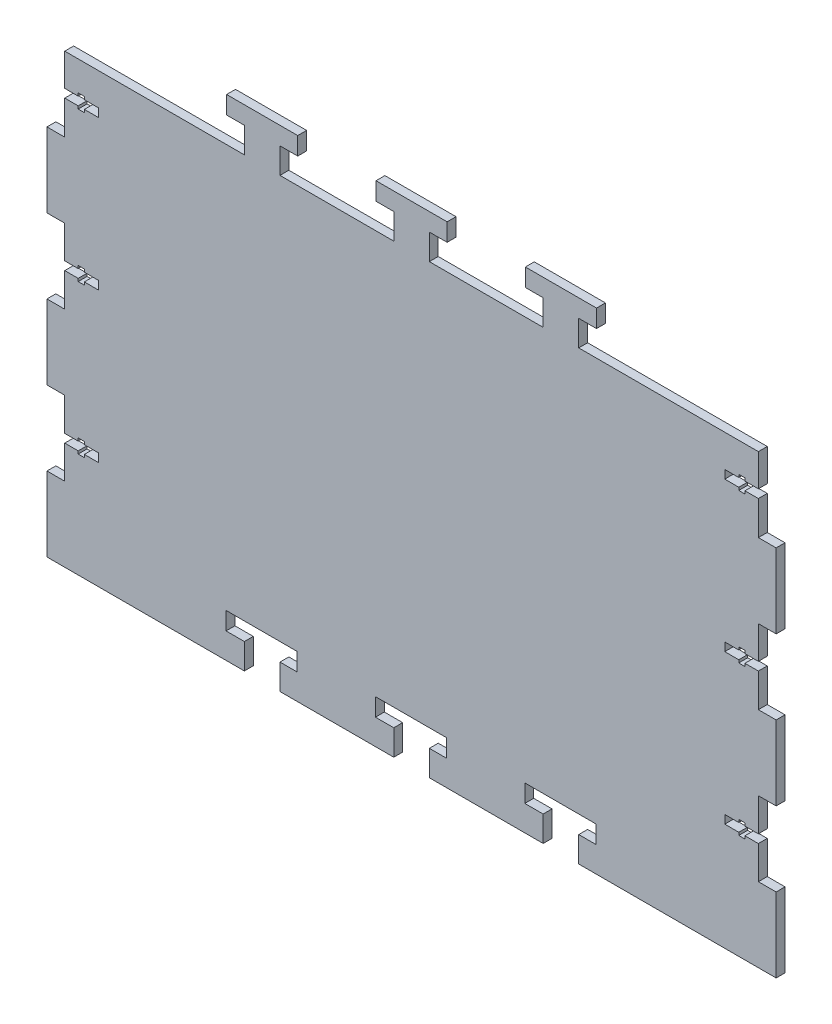
SolidWorks part; units mm, degrees
ref_plane "Front Plane" through (0, 0, 0) normal (0, 0, 1) x (1, 0, 0)
ref_plane "Top Plane" through (0, 0, 0) normal (0, 1, 0) x (1, 0, 0)
ref_plane "Right Plane" through (0, 0, 0) normal (1, 0, 0) x (0, 0, -1)
sketch "Sketch1" plane through (0, 0, 0) normal (0, 0, 1) x (1, 0, 0)
  line L1 (130.175, -79.7965) -> (-130.175, -79.7965)
  line L2 (130.175, -79.7965) -> (130.175, 79.7965)
  line L3 (130.175, 79.7965) -> (-130.175, 79.7965)
  line L4 (-130.175, -79.7965) -> (-130.175, 79.7965)
  line L5 (130.175, -79.7965) -> (-130.175, 79.7965) construction
  line L6 (130.175, 79.7965) -> (-130.175, -79.7965) construction
  point P0 (0, 0)
  dimension "D1" = 260.35
  dimension "D2" = 159.5929
extrude "Boss-Extrude1" add sketch "Sketch1" along normal blind 3.175
sketch "Sketch2" plane through (-130.175, 0, 0) normal (-1, 0, 0) x (0, 0, 1)
  line L0 (0, 79.7965) -> (0, -79.7965) construction
  line L1 (3.175, 79.7965) -> (0, 79.7965)
  line L2 (3.175, 79.7965) -> (3.175, 53.1976)
  line L3 (3.175, 53.1976) -> (0, 53.1976)
  line L4 (0, 79.7965) -> (0, 53.1976)
  dimension "D1" = 26.5988
extrude "Cut-Extrude1" cut sketch "Sketch2" against normal blind 6.35
pattern_linear "LPattern1" count 3 spacing 53.1976 along (0, -1, 0) of "Cut-Extrude1"
sketch "Sketch3" plane through (130.175, 0, 0) normal (1, 0, 0) x (0, 0, -1)
  line L0 (0, -79.7965) -> (0, 79.7965) construction
  line L1 (-3.175, -53.1976) -> (0, -53.1976)
  line L2 (-3.175, -53.1976) -> (-3.175, -26.5988)
  line L3 (-3.175, -26.5988) -> (0, -26.5988)
  line L4 (0, -53.1976) -> (0, -26.5988)
  line L6 (-3.175, 79.7965) -> (0, 79.7965) construction
  point P9 (-1.5875, 79.7965)
  dimension "D1" = 26.5988
  dimension "D2" = 106.3953
extrude "Cut-Extrude3" cut sketch "Sketch3" against normal blind 6.35
pattern_linear "LPattern3" count 3 spacing 53.1976 along (0, 1, 0) of "Cut-Extrude3"
sketch "Sketch5" plane through (-123.825, 0, 0) normal (-1, 0, 0) x (0, 0, 1)
  line L0 (0, -39.8982) -> (3.175, -39.8982) construction
  line L1 (0, -26.5988) -> (0, -53.1976) construction
  line L2 (3.175, -53.1976) -> (3.175, -26.5988) construction
  line L4 (3.175, -41.3982) -> (0, -41.3982)
  line L5 (3.175, -41.3982) -> (3.175, -38.3982)
  line L6 (3.175, -38.3982) -> (0, -38.3982)
  line L7 (0, -41.3982) -> (0, -38.3982)
  line L8 (3.175, -41.3982) -> (0, -38.3982) construction
  line L9 (3.175, -38.3982) -> (0, -41.3982) construction
  point P6 (1.5875, -39.8982)
  dimension "D1" = 3
extrude "Cut-Extrude4" cut sketch "Sketch5" against normal blind 12
sketch "Sketch6" plane through (0, -38.3982, 0) normal (0, -1, 0) x (1, 0, 0)
  line L0 (-111.825, 3.175) -> (-123.825, 3.175) construction
  line L1 (-116.825, 3.175) -> (-119.025, 3.175)
  line L2 (-116.825, 3.175) -> (-116.825, 0)
  line L3 (-116.825, 0) -> (-119.025, 0)
  line L4 (-119.025, 3.175) -> (-119.025, 0)
  line L5 (-111.825, 0) -> (-123.825, 0) construction
  line L6 (-111.825, 3.175) -> (-111.825, 0) construction
  dimension "D1" = 5
  dimension "D2" = 2.2
extrude "Cut-Extrude5" cut sketch "Sketch6" against normal blind 1
sketch "Sketch8" plane through (0, -41.3982, 0) normal (0, 1, 0) x (1, 0, 0)
  line L0 (-111.825, -3.175) -> (-123.825, -3.175) construction
  line L1 (-116.825, -3.175) -> (-119.025, -3.175)
  line L2 (-116.825, -3.175) -> (-116.825, 0)
  line L3 (-116.825, 0) -> (-119.025, 0)
  line L4 (-119.025, -3.175) -> (-119.025, 0)
  line L5 (-111.825, 0) -> (-123.825, 0) construction
  line L6 (-111.825, 0) -> (-111.825, -3.175) construction
  dimension "D1" = 5
  dimension "D2" = 2.2
extrude "Cut-Extrude6" cut sketch "Sketch8" against normal blind 1
pattern_linear "LPattern5" count 3 spacing 53.34 along (0, 1, 0) of "Cut-Extrude4", "Cut-Extrude5", "Cut-Extrude6"
sketch "Sketch9" plane through (123.825, 0, 0) normal (1, 0, 0) x (0, 0, -1)
  line L0 (-3.175, -39.8982) -> (0, -39.8982) construction
  line L1 (-3.175, -26.5988) -> (-3.175, -53.1976) construction
  line L2 (0, -53.1976) -> (0, -26.5988) construction
  line L4 (0, -38.3982) -> (-3.175, -38.3982)
  line L5 (0, -38.3982) -> (0, -41.3982)
  line L6 (0, -41.3982) -> (-3.175, -41.3982)
  line L7 (-3.175, -38.3982) -> (-3.175, -41.3982)
  line L8 (0, -38.3982) -> (-3.175, -41.3982) construction
  line L9 (0, -41.3982) -> (-3.175, -38.3982) construction
  point P6 (-1.5875, -39.8982)
  dimension "D1" = 3
extrude "Cut-Extrude7" cut sketch "Sketch9" against normal blind 12
sketch "Sketch10" plane through (0, -38.3982, 0) normal (0, -1, 0) x (1, 0, 0)
  line L0 (111.825, 3.175) -> (123.825, 3.175) construction
  line L1 (116.825, 3.175) -> (119.025, 3.175)
  line L2 (116.825, 3.175) -> (116.825, 0)
  line L3 (116.825, 0) -> (119.025, 0)
  line L4 (119.025, 3.175) -> (119.025, 0)
  line L5 (111.825, 0) -> (123.825, 0) construction
  line L6 (111.825, 0) -> (111.825, 3.175) construction
  dimension "D1" = 5
  dimension "D2" = 2.2
extrude "Cut-Extrude8" cut sketch "Sketch10" against normal blind 1
sketch "Sketch11" plane through (0, -41.3982, 0) normal (0, 1, 0) x (1, 0, 0)
  line L0 (111.825, -3.175) -> (123.825, -3.175) construction
  line L1 (116.825, -3.175) -> (119.025, -3.175)
  line L2 (116.825, -3.175) -> (116.825, 0)
  line L3 (116.825, 0) -> (119.025, 0)
  line L4 (119.025, -3.175) -> (119.025, 0)
  line L5 (111.825, 0) -> (123.825, 0) construction
  line L6 (111.825, -3.175) -> (111.825, 0) construction
  dimension "D1" = 5
  dimension "D2" = 2.2
extrude "Cut-Extrude9" cut sketch "Sketch11" against normal blind 1
pattern_linear "LPattern6" count 3 spacing 53.34 along (0, 1, 0) of "Cut-Extrude7", "Cut-Extrude8", "Cut-Extrude9"
sketch "Sketch4" plane through (0, 0, 3.175) normal (0, 0, 1) x (1, 0, 0)
  line L0 (0, 79.7965) -> (0, -79.7965) construction
  line L1 (123.825, 79.7965) -> (-123.825, 79.7965) construction
  line L2 (-130.175, -79.7965) -> (130.175, -79.7965) construction
  line L3 (-6.35, -79.7965) -> (-6.35, -70.6851)
  line L4 (-130.175, -79.7965) -> (130.175, -79.7965) construction
  line L5 (-6.35, -70.6851) -> (-12.8996, -70.6851)
  line L6 (-12.8996, -70.6851) -> (-12.8996, -64.3351)
  line L7 (-12.8996, -64.3351) -> (12.5004, -64.3351)
  line L8 (12.5004, -64.3351) -> (12.5004, -70.6851)
  line L9 (12.5004, -70.6851) -> (6.35, -70.6851)
  line L10 (6.35, -70.6851) -> (6.35, -79.7965)
  line L11 (-6.35, -79.7965) -> (6.35, -79.7965)
  dimension "D1" = 25.4
  dimension "D2" = 12.7
  dimension "D3" = 6.35
  dimension "D4" = 6.35
extrude "Cut-Extrude10" cut sketch "Sketch4" against normal through all
pattern_linear "LPattern7" count 2 spacing 53.34 along (-1, 0, 0) of "Cut-Extrude10"
pattern_linear "LPattern8" count 2 spacing 53.34 along (1, 0, 0) of "Cut-Extrude10"
sketch "Sketch15" plane through (0, 79.7965, 0) normal (0, 1, 0) x (1, 0, 0)
  line L0 (0, -3.175) -> (0, 0) construction
  line L1 (123.825, -3.175) -> (-123.825, -3.175) construction
  line L2 (123.825, 0) -> (-123.825, 0) construction
  line L4 (6.35, -3.175) -> (-6.35, -3.175)
  line L5 (6.35, -3.175) -> (6.35, 0)
  line L6 (6.35, 0) -> (-6.35, 0)
  line L7 (-6.35, -3.175) -> (-6.35, 0)
  line L8 (6.35, -3.175) -> (-6.35, 0) construction
  line L9 (6.35, 0) -> (-6.35, -3.175) construction
  point P6 (0, -1.5875)
  dimension "D1" = 12.7
extrude "Boss-Extrude2" add sketch "Sketch15" along normal blind 9.144
sketch "Sketch16" plane through (0, 88.9405, 0) normal (0, 1, 0) x (1, 0, 0)
  line L0 (0, -3.175) -> (0, 0) construction
  line L1 (-6.35, -3.175) -> (6.35, -3.175) construction
  line L2 (6.35, 0) -> (-6.35, 0) construction
  line L4 (12.7, -3.175) -> (-12.7, -3.175)
  line L5 (12.7, -3.175) -> (12.7, 0)
  line L6 (12.7, 0) -> (-12.7, 0)
  line L7 (-12.7, -3.175) -> (-12.7, 0)
  line L8 (12.7, -3.175) -> (-12.7, 0) construction
  line L9 (12.7, 0) -> (-12.7, -3.175) construction
  point P6 (0, -1.5875)
  dimension "D1" = 25.4
extrude "Boss-Extrude3" add sketch "Sketch16" along normal blind 6.35
pattern_linear "LPattern9" count 2 spacing 53.34 along (1, 0, 0) of "Boss-Extrude2", "Boss-Extrude3"
pattern_linear "LPattern10" count 2 spacing 53.34 along (-1, 0, 0) of "Boss-Extrude2", "Boss-Extrude3"
